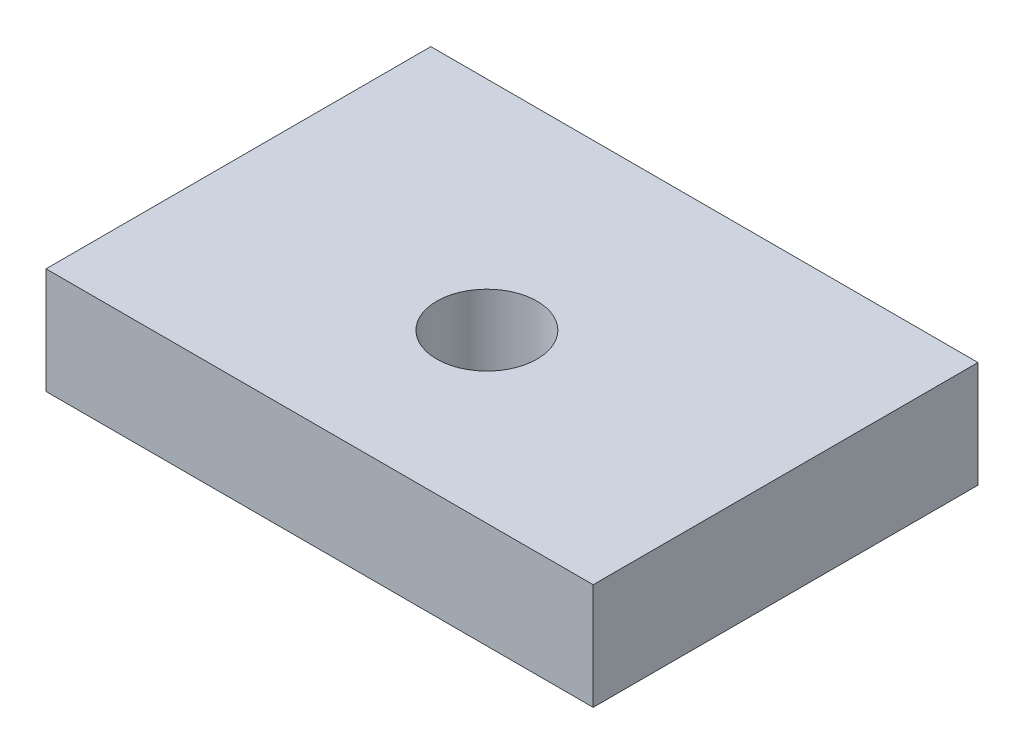
SolidWorks part; units mm, degrees
ref_plane "Front Plane" through (0, 0, 0) normal (0, 0, 1) x (1, 0, 0)
ref_plane "Top Plane" through (0, 0, 0) normal (0, 1, 0) x (1, 0, 0)
ref_plane "Right Plane" through (0, 0, 0) normal (1, 0, 0) x (0, 0, -1)
sketch "Sketch1" plane through (0, 0, 0) normal (0, 1, 0) x (1, 0, 0)
  line L0 (-16.35, 10) -> (16.35, 10) construction
  line L1 (-16.35, -10) -> (16.35, -10)
  line L2 (-16.35, -10) -> (-16.35, 13)
  line L3 (-16.35, 13) -> (16.35, 13)
  line L4 (16.35, -10) -> (16.35, 13)
  line L5 (0, 10) -> (0, -10) construction
  line L6 (-10, 0) -> (10, 0) construction
  circle A0 centre (0, 0) radius 3
  point P4 (0, -10)
  dimension "D4" = 6
  dimension "D1" = 6.35
  dimension "D2" = 3
  dimension "D3" = 20
  dimension "D5" = 20
extrude "Boss-Extrude1" add sketch "Sketch1" along normal mid plane 6.35
